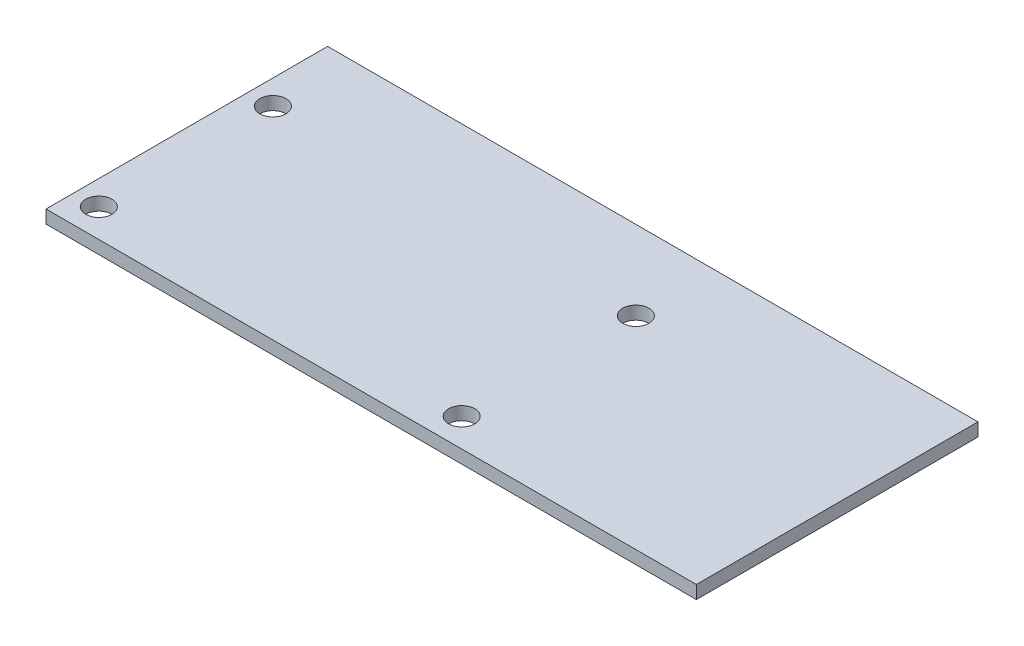
SolidWorks part; units mm, degrees
ref_plane "Front Plane" through (0, 0, 0) normal (0, 0, 1) x (1, 0, 0)
ref_plane "Top Plane" through (0, 0, 0) normal (0, 1, 0) x (1, 0, 0)
ref_plane "Right Plane" through (0, 0, 0) normal (1, 0, 0) x (0, 0, -1)
sketch "Sketch1" plane through (0, 0, 0) normal (0, 1, 0) x (1, 0, 0)
  line L1 (0, 0) -> (78.74, 0)
  line L2 (0, 0) -> (0, 34.0995)
  line L3 (0, 34.0995) -> (78.74, 34.0995)
  line L4 (78.74, 0) -> (78.74, 34.0995)
  dimension "D1" = 34.0995
  dimension "D2" = 78.74
extrude "Boss-Extrude1" add sketch "Sketch1" along normal blind 1.5875 contours L3 L4 L1 L2
sketch "Sketch2" plane through (0, 1.5875, 0) normal (0, 1, 0) x (1, 0, 0)
  line L0 (2.9591, 3.429) -> (46.9011, 3.429) construction
  line L1 (46.9011, 3.429) -> (46.9011, 24.511) construction
  line L2 (46.9011, 24.511) -> (2.9591, 24.511) construction
  line L3 (2.9591, 24.511) -> (2.9591, 3.429) construction
  line L4 (46.9011, 1.8415) -> (46.9011, 0) construction
  line L5 (0, 0) -> (78.74, 0) construction
  line L6 (1.3716, 3.429) -> (0, 3.429) construction
  line L7 (0, 0) -> (0, 34.0995) construction
  circle A0 centre (2.9591, 24.511) radius 1.5875
  circle A1 centre (46.9011, 24.511) radius 1.5875
  circle A2 centre (2.9591, 3.429) radius 1.5875
  circle A3 centre (46.9011, 3.429) radius 1.5875
  dimension "D3" = 3.175
  dimension "D1" = 43.942
  dimension "D2" = 21.082
  dimension "D4" = 1.8415
  dimension "D5" = 1.3716
extrude "Cut-Extrude1" cut sketch "Sketch2" against normal through all
